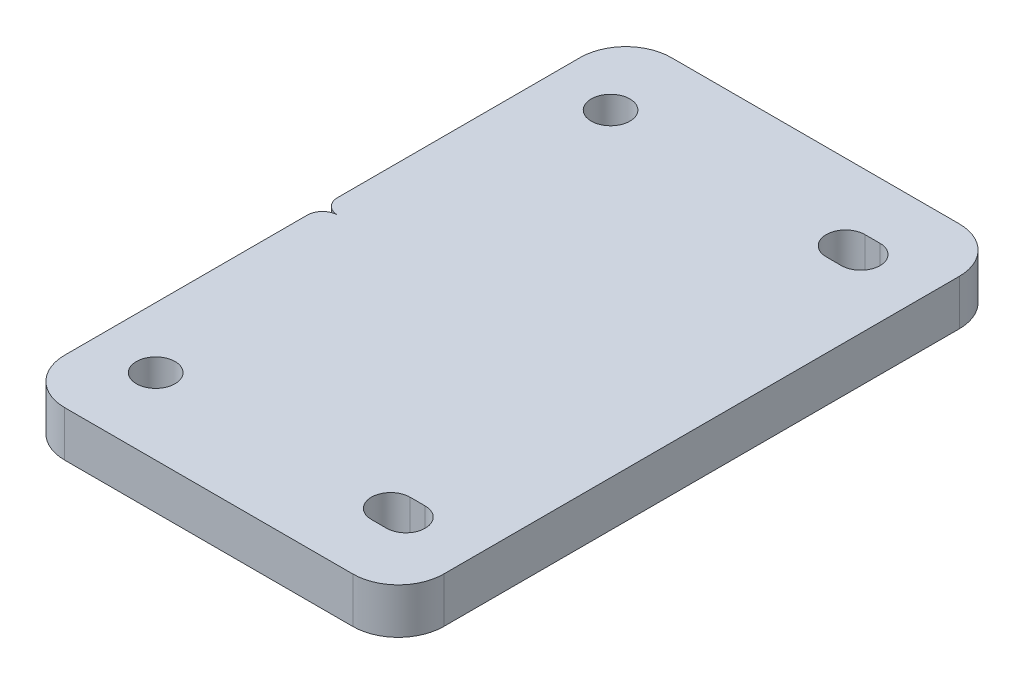
SolidWorks part; units mm, degrees
material "Клен"
ref_plane "Спереди" through (0, 0, 0) normal (0, 0, 1) x (1, 0, 0)
ref_plane "Сверху" through (0, 0, 0) normal (0, 1, 0) x (1, 0, 0)
ref_plane "Справа" through (0, 0, 0) normal (1, 0, 0) x (0, 0, -1)
sketch "Эскиз1" plane through (0, 0, 0) normal (0, 1, 0) x (1, 0, 0)
  line L0 (-41.181, -0.0464) -> (44.1026, -0.0464) construction
  line L10 (-19, -40) -> (19, -40)
  line L11 (-25, -34) -> (-25, 34)
  line L12 (-19, 40) -> (19, 40)
  line L13 (25, -34) -> (25, 34)
  line L14 (-25, -40) -> (25, 40) construction
  line L15 (-25, 40) -> (25, -40) construction
  arc A4 (19, 40) -> (25, 34) centre (19, 34) cw
  arc A5 (19, -40) -> (25, -34) centre (19, -34) ccw
  arc A6 (-19, -40) -> (-25, -34) centre (-19, -34) cw
  arc A7 (-25, 34) -> (-19, 40) centre (-19, 34) cw
  point P0 (0, 0)
  dimension "D1" = 6
  dimension "D2" = 80
  dimension "D3" = 50
extrude "Бобышка-Вытянуть1" add sketch "Эскиз1" along normal blind 6
sketch "Эскиз2" plane through (0, 0, 0) normal (0, -1, 0) x (1, 0, 0)
  line L0 (0, -37.0349) -> (0, 29.2907) construction
  line L1 (16, -30) -> (14, -30) construction
  line L2 (16, -32.55) -> (14, -32.55)
  line L3 (16, -27.45) -> (14, -27.45)
  line L6 (-46.1924, 0) -> (55.6646, 0) construction
  line L7 (16, 30) -> (14, 30) construction
  line L8 (16, 32.55) -> (14, 32.55)
  line L9 (16, 27.45) -> (14, 27.45)
  line L10 (-25, -34) -> (-25, 34) construction
  line L11 (19, -40) -> (-19, -40) construction
  circle A0 centre (-17, -30) radius 2.55
  arc A1 (16, -32.55) -> (16, -27.45) centre (16, -30) ccw
  arc A2 (14, -27.45) -> (14, -32.55) centre (14, -30) ccw
  arc A3 (16, 32.55) -> (16, 27.45) centre (16, 30) cw
  arc A4 (14, 27.45) -> (14, 32.55) centre (14, 30) cw
  circle A5 centre (-17, 30) radius 2.55
  point P7 (15, -30)
  point P12 (15, -32.55)
  point P21 (15, 30)
  dimension "D1" = 5.1
  dimension "D2" = 5.1
  dimension "D3" = 2
  dimension "D4" = 33
  dimension "D5" = 8
  dimension "D6" = 10
extrude "Вырез-Вытянуть1" cut sketch "Эскиз2" against normal through all
sketch "Эскиз3" plane through (0, 0, 0) normal (0, -1, 0) x (1, 0, 0)
  line L0 (-23, 0) -> (27.7687, 0) construction
  line L1 (-25, -34) -> (-25, 34) construction
  line L2 (-25, -2) -> (-25, 2)
  arc A0 (-23, 0) -> (-25, -2) centre (-23, -2) ccw
  arc A1 (-23, 0) -> (-25, 2) centre (-23, 2) cw
  point P3 (-25, -2)
  point P4 (-23, 0)
  point P7 (-25, 2)
  dimension "D2" = 2
  dimension "D1" = 2
extrude "Вырез-Вытянуть2" cut sketch "Эскиз3" against normal through all
equation "\"D2@Эскиз2\"=\"D1@Эскиз2\""
